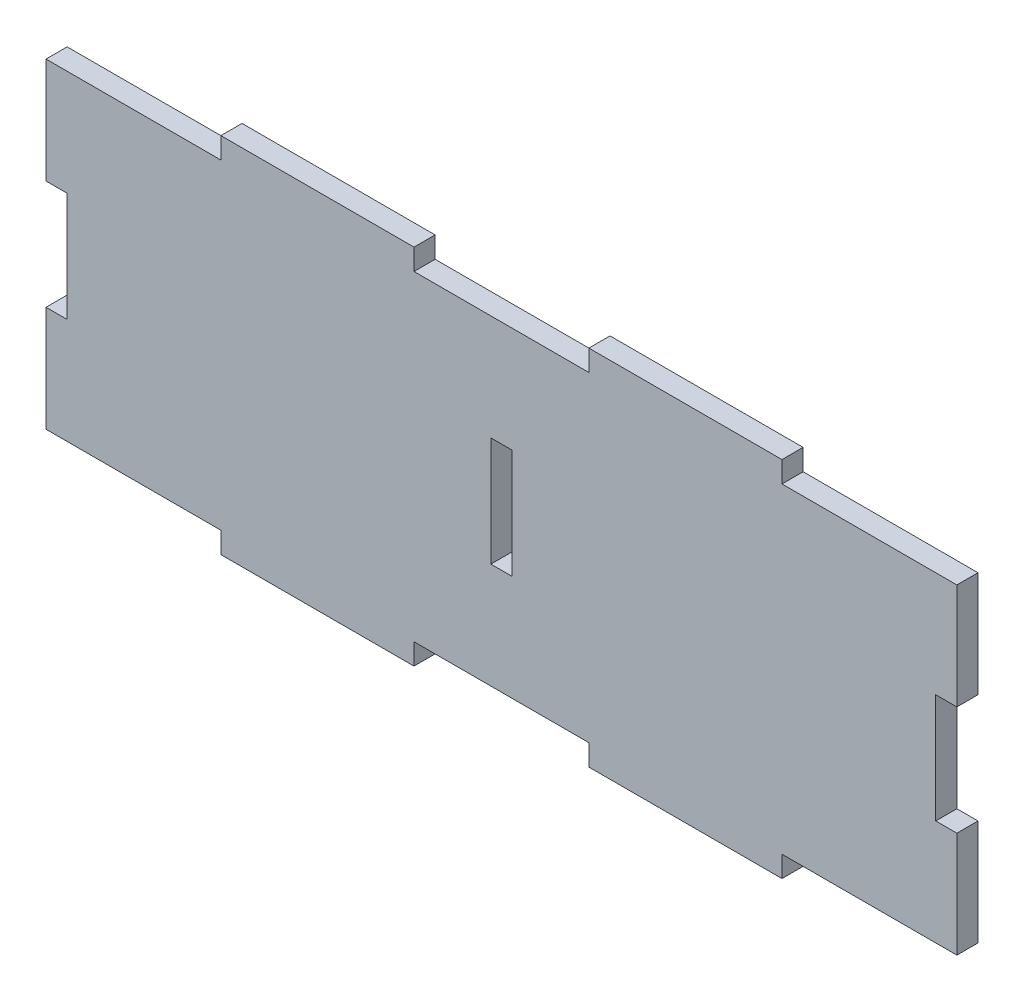
SolidWorks part; units mm, degrees
material "Бальса"
ref_plane "Спереди" through (0, 0, 0) normal (0, 0, 1) x (1, 0, 0)
ref_plane "Сверху" through (0, 0, 0) normal (0, 1, 0) x (1, 0, 0)
ref_plane "Справа" through (0, 0, 0) normal (1, 0, 0) x (0, 0, -1)
sketch "Эскиз1" plane through (0, 0, 0) normal (0, 0, 1) x (1, 0, 0)
  line L1 (0, 0) -> (250, 0)
  line L2 (0, 0) -> (0, 88)
  line L3 (0, 88) -> (250, 88)
  line L4 (250, 0) -> (250, 88)
  dimension "D1" = 250
  dimension "D2" = 88
extrude "Бобышка-Вытянуть1" add sketch "Эскиз1" along normal blind 5.8
sketch "Эскиз2" plane through (0, 0, 0) normal (0, 0, -1) x (-1, 0, 0)
  line L0 (-250, 0) -> (-250, 88) construction
  line L1 (-250, 59) -> (-244.2, 59)
  line L2 (-250, 59) -> (-250, 29)
  line L3 (-250, 29) -> (-244.2, 29)
  line L4 (-244.2, 59) -> (-244.2, 29)
  line L5 (0, 88) -> (0, 0) construction
  line L6 (-127.9, 59) -> (-122.1, 59)
  line L7 (-127.9, 59) -> (-127.9, 29)
  line L8 (-127.9, 29) -> (-122.1, 29)
  line L9 (-122.1, 59) -> (-122.1, 29)
  line L10 (0, 59) -> (-5.8, 59)
  line L11 (0, 59) -> (0, 29)
  line L12 (0, 29) -> (-5.8, 29)
  line L13 (-5.8, 59) -> (-5.8, 29)
  line L14 (-125, 88) -> (-125, 59) construction
  line L15 (-250, 88) -> (0, 88) construction
  line L16 (-244.2, 44) -> (-127.9, 44) construction
  line L17 (-122.1, 44) -> (-5.8, 44) construction
  line L18 (-244.2, 44) -> (-250, 44) construction
  point P24 (-250, 44)
  point P30 (-244.2, 59)
  dimension "D1" = 5.8
  dimension "D2" = 30
  dimension "D3" = 30
  dimension "D4" = 30
extrude "Вырез-Вытянуть1" cut sketch "Эскиз2" against normal up to next
sketch "Эскиз3" plane through (0, 0, 5.8) normal (0, 0, 1) x (1, 0, 0)
  line L0 (250, 88) -> (0, 88) construction
  line L1 (48, 88) -> (101, 88)
  line L2 (48, 88) -> (48, 93.8)
  line L3 (48, 93.8) -> (101, 93.8)
  line L4 (101, 88) -> (101, 93.8)
  line L5 (0, 0) -> (250, 0) construction
  line L6 (149, 88) -> (202, 88)
  line L7 (149, 88) -> (149, 93.8)
  line L8 (149, 93.8) -> (202, 93.8)
  line L9 (202, 88) -> (202, 93.8)
  line L10 (48, 0) -> (101, 0)
  line L11 (48, 0) -> (48, -5.8)
  line L12 (48, -5.8) -> (101, -5.8)
  line L13 (101, 0) -> (101, -5.8)
  line L14 (250, 59) -> (250, 88) construction
  line L15 (149, 0) -> (202, 0)
  line L16 (149, 0) -> (149, -5.8)
  line L17 (149, -5.8) -> (202, -5.8)
  line L18 (202, 0) -> (202, -5.8)
  dimension "D1" = 48
  dimension "D2" = 48
  dimension "D3" = 48
  dimension "D4" = 5.8
extrude "Бобышка-Вытянуть2" add sketch "Эскиз3" against normal up to surface (5.8 mm away) up to face at (125, 44, 0)
